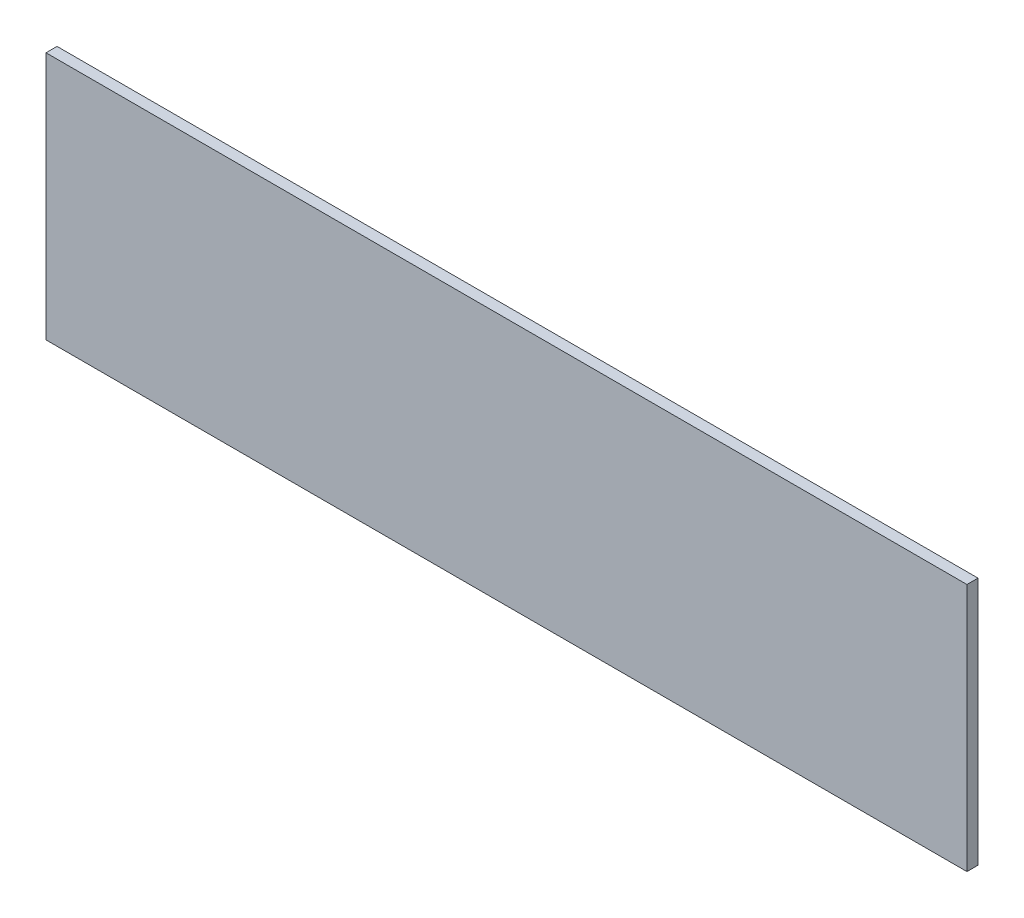
SolidWorks part; units mm, degrees
material "Pine"
ref_plane "Front Plane" through (0, 0, 0) normal (0, 0, 1) x (1, 0, 0)
ref_plane "Top Plane" through (0, 0, 0) normal (0, 1, 0) x (1, 0, 0)
ref_plane "Right Plane" through (0, 0, 0) normal (1, 0, 0) x (0, 0, -1)
sketch "Sketch1" plane through (0, 0, 0) normal (0, 0, 1) x (1, 0, 0)
  line L1 (0, 0) -> (500, 0)
  line L2 (0, 0) -> (0, 135)
  line L3 (0, 135) -> (500, 135)
  line L4 (500, 0) -> (500, 135)
  dimension "D1" = 500
  dimension "D2" = 135
extrude "Boss-Extrude1" add sketch "Sketch1" along normal blind 6
